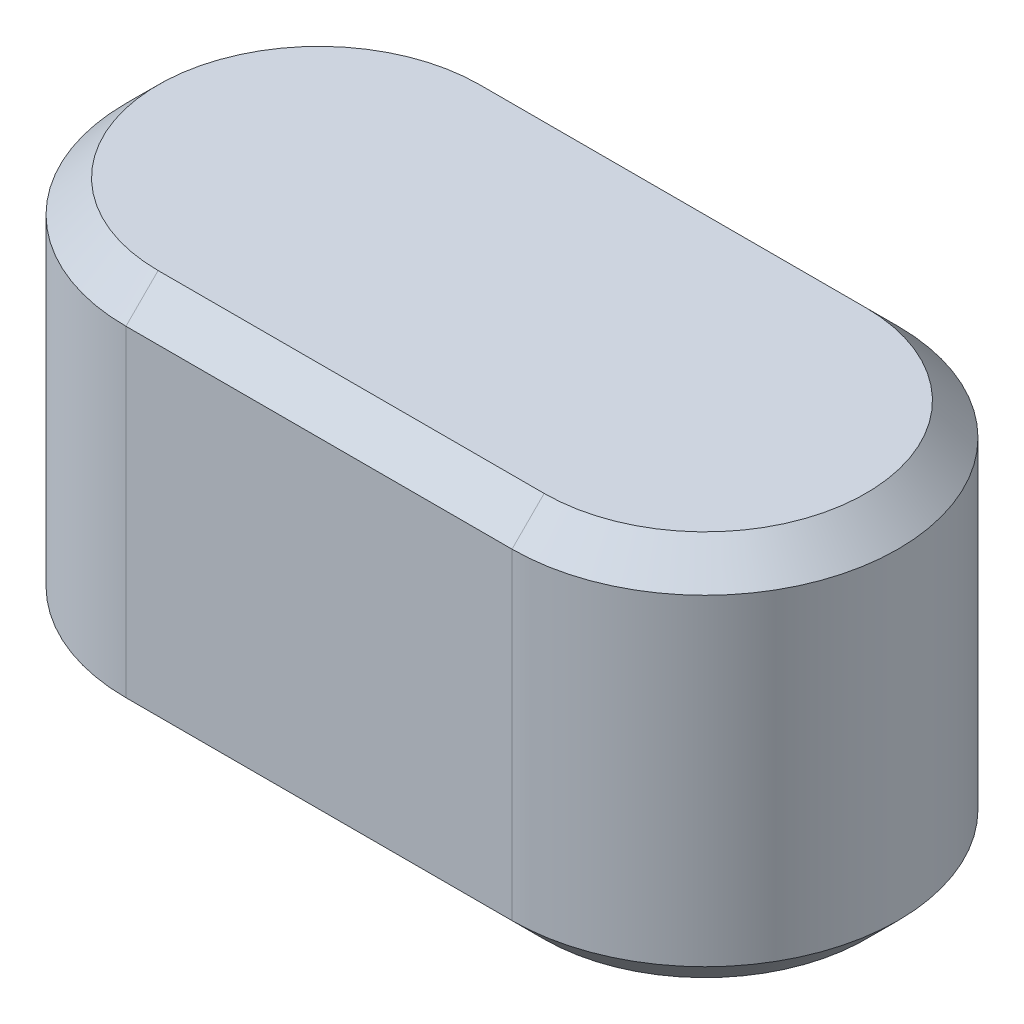
SolidWorks part; units mm, degrees
ref_plane "前视基准面" through (0, 0, 0) normal (0, 0, 1) x (1, 0, 0)
ref_plane "上视基准面" through (0, 0, 0) normal (0, 1, 0) x (1, 0, 0)
ref_plane "右视基准面" through (0, 0, 0) normal (1, 0, 0) x (0, 0, -1)
sketch "草图1" plane through (0, 0, 0) normal (0, 1, 0) x (1, 0, 0)
  line L0 (0, 0) -> (6, 0) construction
  line L1 (-55, 0) -> (55, 0) construction
  line L2 (0, 3) -> (6, 3)
  line L3 (0, -3) -> (6, -3)
  arc A0 (0, 3) -> (0, -3) centre (0, 0) ccw
  arc A1 (6, -3) -> (6, 3) centre (6, 0) ccw
  point P5 (3, 0)
  dimension "D1" = 12
  dimension "D2" = 6
extrude "凸台-拉伸1" add sketch "草图1" along normal blind 6
chamfer "倒角1" distance 0.5 angle 45 8 edges at (3, 0, 3) (9, 0, 0) (3, 0, -3) (-3, 0, 0) (3, 6, -3) (9, 6, 0) (3, 6, 3) (-3, 6, 0)
